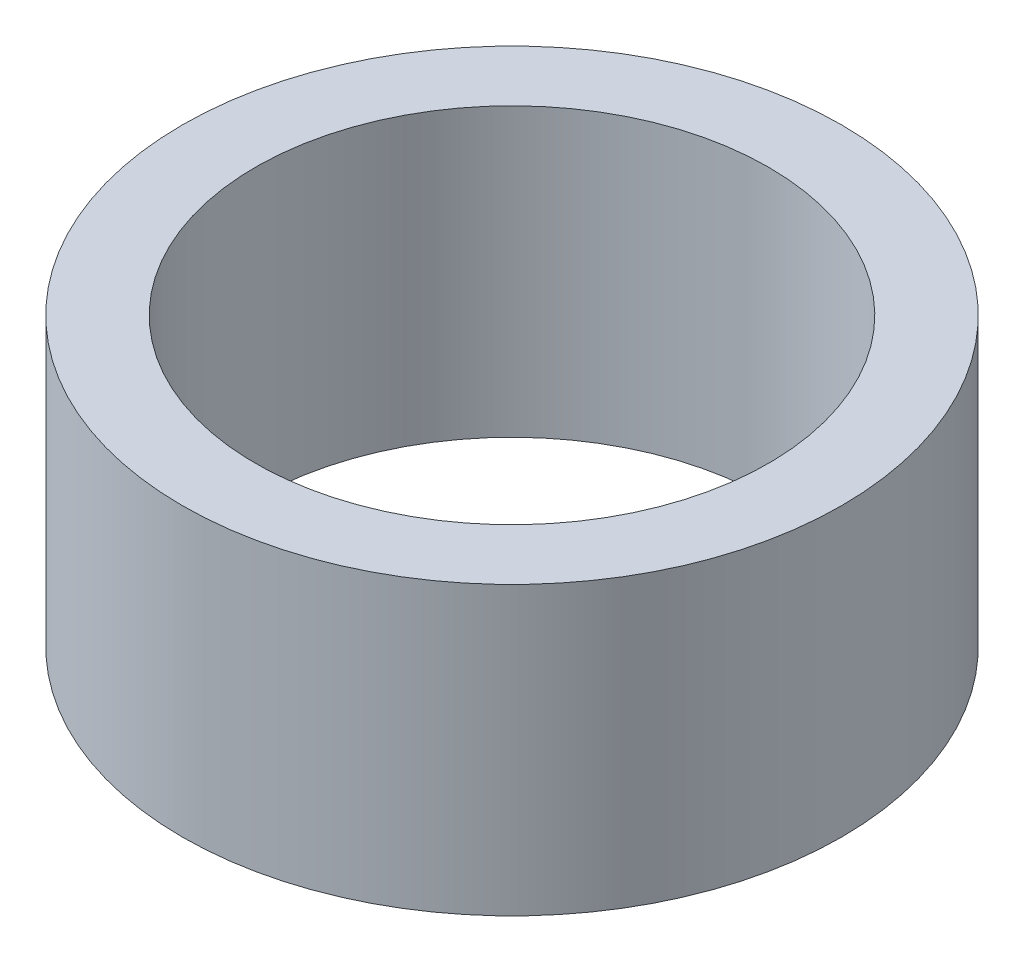
SolidWorks part; units mm, degrees
ref_plane "Front Plane" through (0, 0, 0) normal (0, 0, 1) x (1, 0, 0)
ref_plane "Top Plane" through (0, 0, 0) normal (0, 1, 0) x (1, 0, 0)
ref_plane "Right Plane" through (0, 0, 0) normal (1, 0, 0) x (0, 0, -1)
sketch "Sketch1" plane through (0, 0, 0) normal (0, 1, 0) x (1, 0, 0)
  circle A0 centre (0, 0) radius 4.1999
  circle A1 centre (0, 0) radius 5.3975
  dimension "D1" = 8.3998
  dimension "D2" = 10.795
extrude "Boss-Extrude1" add sketch "Sketch1" along normal blind 4.6995
